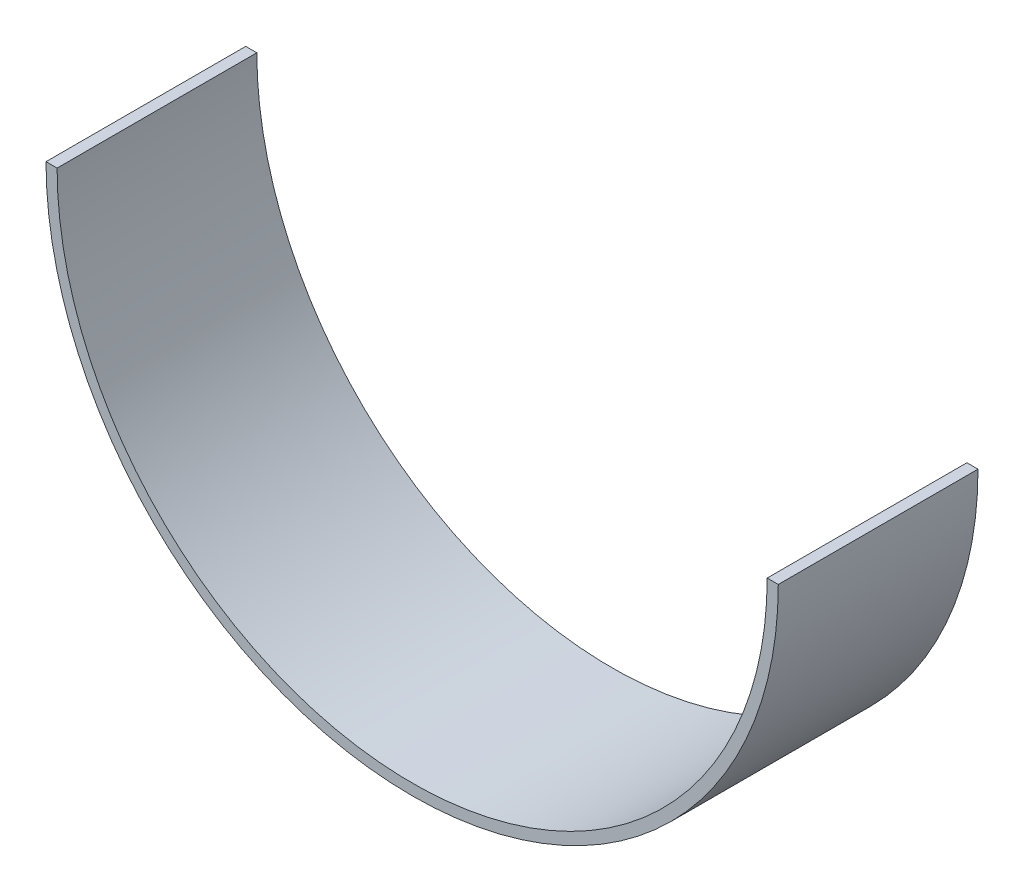
SolidWorks part; units mm, degrees
ref_plane "Alzado" through (0, 0, 0) normal (0, 0, 1) x (1, 0, 0)
ref_plane "Planta" through (0, 0, 0) normal (0, 1, 0) x (1, 0, 0)
ref_plane "Vista lateral" through (0, 0, 0) normal (1, 0, 0) x (0, 0, -1)
sketch "Croquis1" plane through (0, 0, 0) normal (0, 0, 1) x (1, 0, 0)
  line L0 (0, 0) -> (-33, 0) construction
  line L1 (0, 0) -> (33, 0) construction
  line L2 (-32, 0) -> (-33, 0)
  line L3 (33, 0) -> (32, 0)
  arc A0 (-32, 0) -> (32, 0) centre (0, 0) ccw
  arc A1 (-33, 0) -> (33, 0) centre (0, 0) ccw
  dimension "D1" = 66
  dimension "D2" = 64
extrude "Saliente-Extruir1" add sketch "Croquis1" along normal mid plane 18
